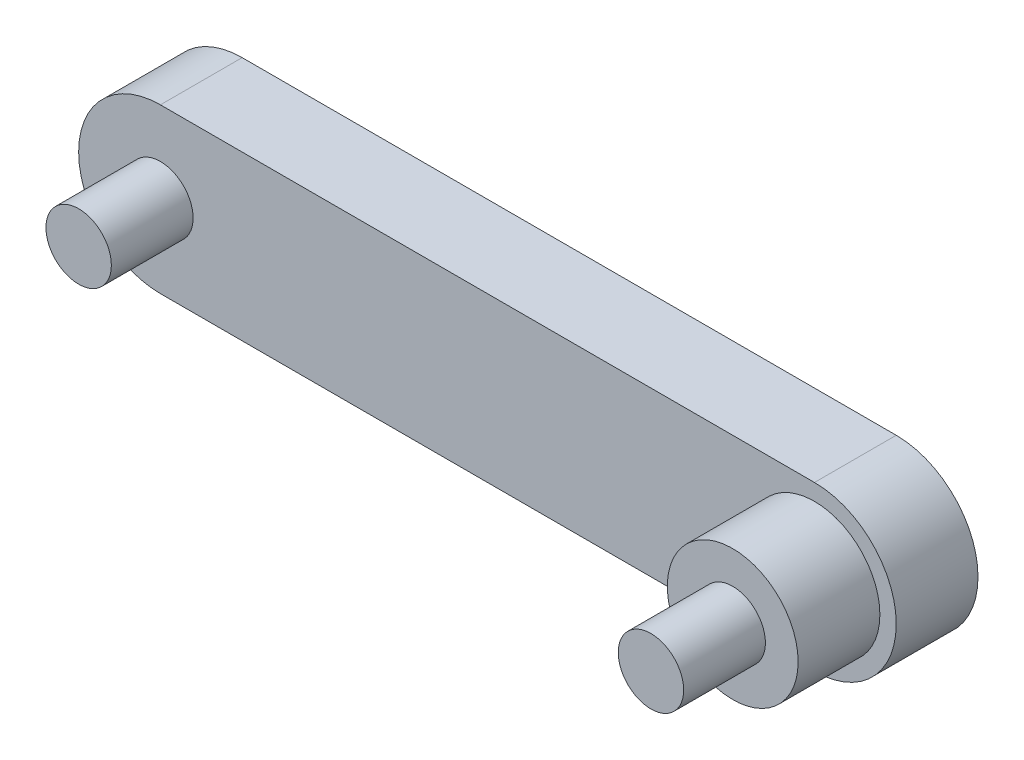
SolidWorks part; units mm, degrees
ref_plane "Alzado" through (0, 0, 0) normal (0, 0, 1) x (1, 0, 0)
ref_plane "Planta" through (0, 0, 0) normal (0, 1, 0) x (1, 0, 0)
ref_plane "Vista lateral" through (0, 0, 0) normal (1, 0, 0) x (0, 0, -1)
sketch "Croquis1" plane through (0, 0, 0) normal (0, 0, 1) x (1, 0, 0)
  line L1 (-19.0853, 5.8095) -> (20.9147, 5.8095)
  line L3 (-19.0853, -4.1905) -> (20.9147, -4.1905)
  arc A0 (-19.0853, 5.8095) -> (-19.0853, -4.1905) centre (-19.0853, 0.8095) ccw
  arc A1 (20.9147, -4.1905) -> (20.9147, 5.8095) centre (20.9147, 0.8095) ccw
  dimension "D1" = 5
  dimension "D3" = 5
  dimension "D2" = 40
extrude "Saliente-Extruir1" add sketch "Croquis1" along normal blind 5
sketch "Croquis2" plane through (0, 0, 5) normal (0, 0, 1) x (1, 0, 0)
  circle A0 centre (-19.0853, 0.8095) radius 2
  circle A1 centre (20.9147, 0.8095) radius 4
  dimension "D2" = 4
  dimension "D3" = 8
  dimension "D1" = 40
extrude "Saliente-Extruir2" add sketch "Croquis2" along normal blind 5
sketch "Croquis3" plane through (0, 0, 10) normal (0, 0, 1) x (1, 0, 0)
  circle A0 centre (20.9147, 0.8095) radius 2
  dimension "D1" = 4
extrude "Saliente-Extruir3" add sketch "Croquis3" along normal blind 5
